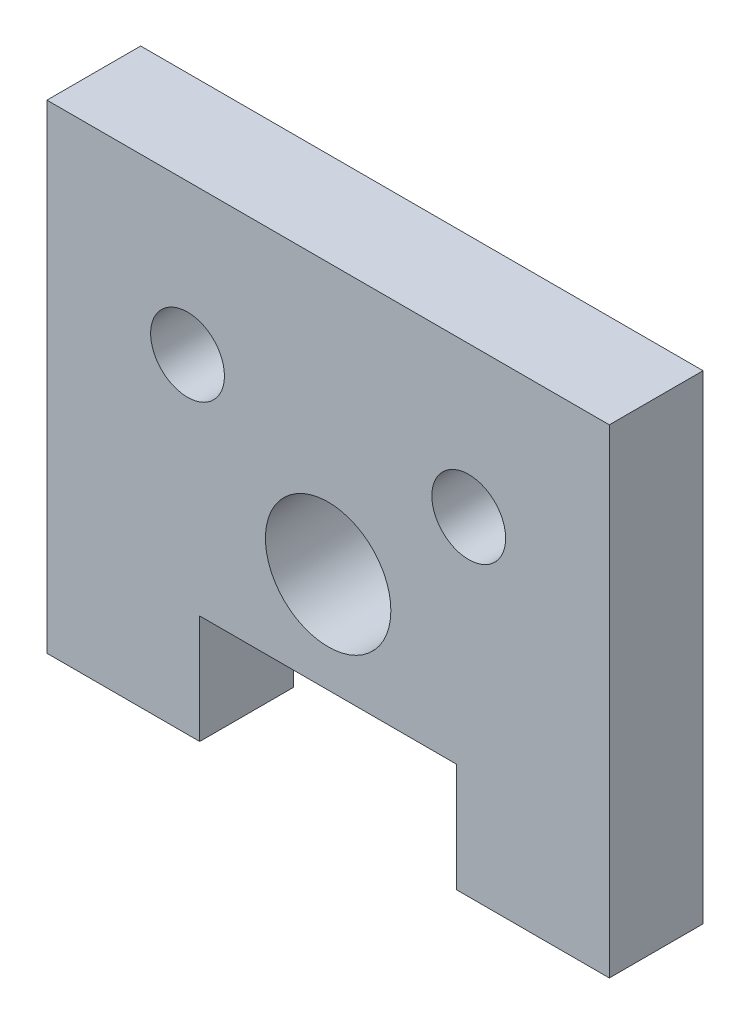
SolidWorks part; units mm, degrees
material "Acrylic (Medium-high impact)"
ref_plane "Front Plane" through (0, 0, 0) normal (0, 0, 1) x (1, 0, 0)
ref_plane "Top Plane" through (0, 0, 0) normal (0, 1, 0) x (1, 0, 0)
ref_plane "Right Plane" through (0, 0, 0) normal (1, 0, 0) x (0, 0, -1)
sketch "Sketch1" plane through (0, 0, 0) normal (0, 0, 1) x (1, 0, 0)
  line L0 (-17.399, -36.576) -> (-17.399, -21.844)
  line L1 (38.1, -36.576) -> (17.399, -36.576)
  line L2 (38.1, -36.576) -> (38.1, 34.544)
  line L4 (-38.1, -36.576) -> (-38.1, 36.576)
  line L5 (-17.399, -21.844) -> (17.399, -21.844)
  line L6 (17.399, -21.844) -> (17.399, -36.576)
  line L7 (-17.399, -36.576) -> (-38.1, -36.576)
  line L8 (0, -21.844) -> (0, -16.764)
  line L9 (-19.05, 28.3364) -> (-38.1, 28.3364)
  line L10 (-19.05, 28.3364) -> (38.1, 28.3364)
  circle A3 centre (0, -8.264) radius 8.5
  circle A4 centre (-19.05, 7.992) radius 5
  circle A5 centre (19.05, 7.992) radius 5
  point P0 (0, 0)
  point P6 (-38.1, 0)
  point P18 (0, -21.844)
  dimension "D3" = 17
  dimension "D5" = 10
  dimension "D8" = 34.798
  dimension "D9" = 14.732
  dimension "D10" = 5.08
  dimension "D4" = 16.256
  dimension "D6" = 19.05
  dimension "D7" = 19.05
  dimension "D2" = 76.2
extrude "Boss-Extrude2" add sketch "Sketch1" along normal blind 12.7
equation "\"D7@Sketch1\"=\"D6@Sketch1\""
